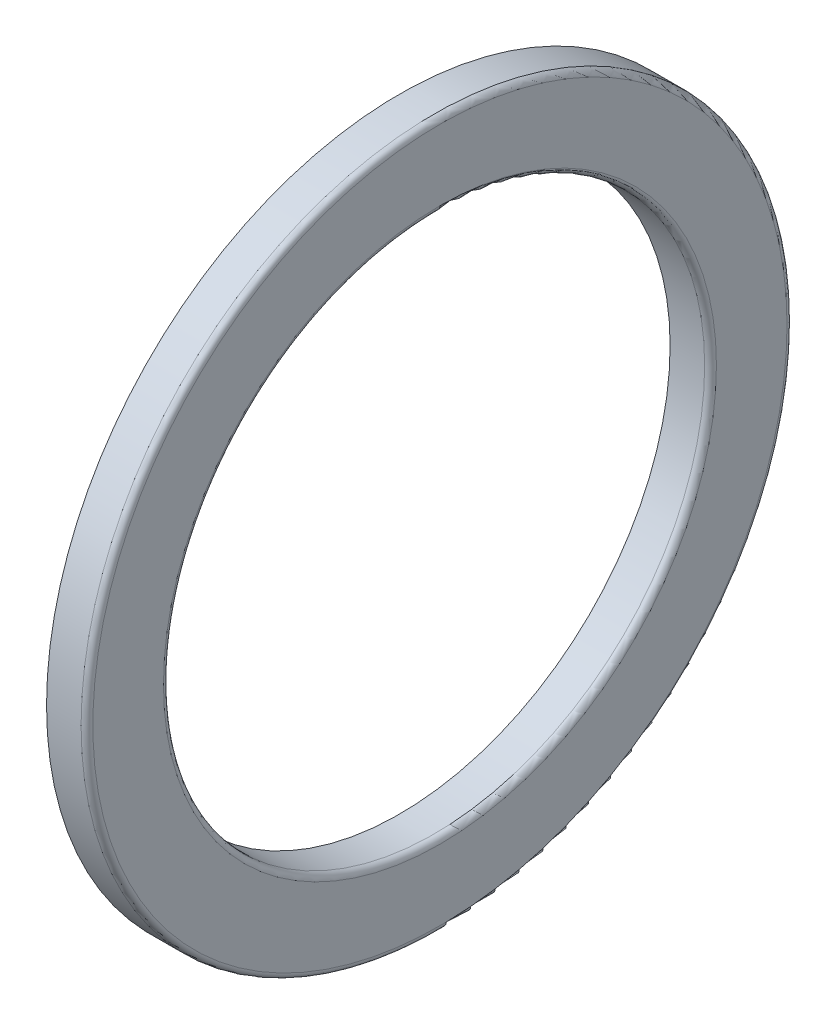
SolidWorks part; units mm, degrees
ref_plane "Front Plane" through (0, 0, 0) normal (0, 0, 1) x (1, 0, 0)
ref_plane "Top Plane" through (0, 0, 0) normal (0, 1, 0) x (1, 0, 0)
ref_plane "Right Plane" through (0, 0, 0) normal (1, 0, 0) x (0, 0, -1)
sketch "Sketch1" plane through (0, 0, 0) normal (0, 0, 1) x (1, 0, 0)
  line L0 (15.1276, 60) -> (15.1276, 55.5957)
  line L1 (15.1276, 49.4043) -> (15.1276, 46)
  line L2 (15.1276, 46) -> (21, 46)
  line L3 (22, 47) -> (22, 59)
  line L4 (21, 60) -> (15.1276, 60)
  line L5 (15.1276, 0) -> (22.0013, 0) construction
  arc A0 (15.1276, 55.5957) -> (15.1276, 49.4043) centre (11, 52.5) cw
  arc A1 (21, 46) -> (22, 47) centre (21, 47) ccw
  arc A2 (22, 59) -> (21, 60) centre (21, 59) ccw
revolve "Revolve1" add sketch "Sketch1" angle 360 about L5
